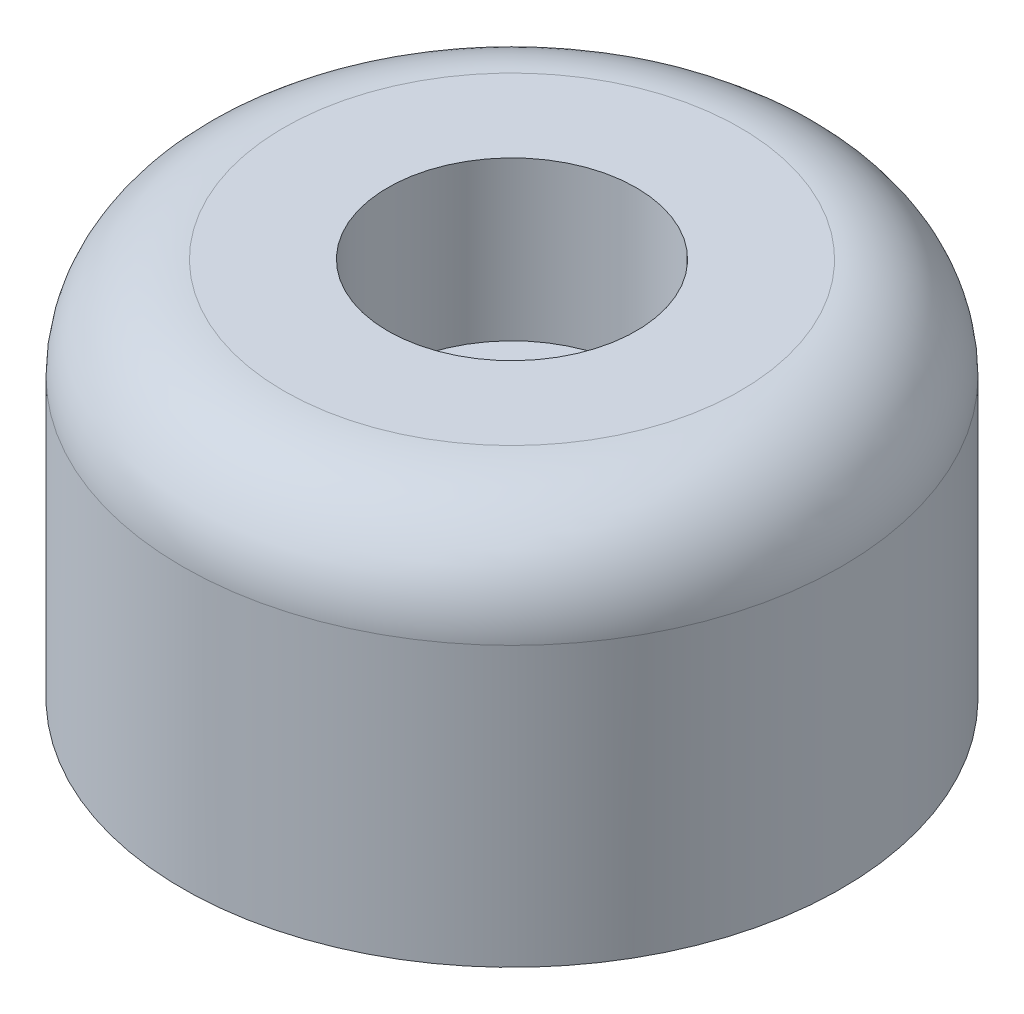
SolidWorks part; units mm, degrees
ref_plane "Front Plane" through (0, 0, 0) normal (0, 0, 1) x (1, 0, 0)
ref_plane "Top Plane" through (0, 0, 0) normal (0, 1, 0) x (1, 0, 0)
ref_plane "Right Plane" through (0, 0, 0) normal (1, 0, 0) x (0, 0, -1)
sketch "Croquis1" plane through (0, 0, 0) normal (0, 1, 0) x (1, 0, 0)
  circle A0 centre (0, 0) radius 16.51
  dimension "D1" = 33.02
extrude "Saliente-Extruir1" add sketch "Croquis1" along normal blind 19.05
hole_wizard "Refrentado para tornillo con cabeza hueca de 5/161" positions "Croquis4" profile "Croquis3" counterbore size "5/16" standard "Ansi Inch"
sketch "Croquis4" plane through (0, 19.05, 0) normal (0, 1, 0) x (1, 0, 0)
  point P0 (0, 0)
sketch "Croquis3" plane through (0, 19.05, 0) normal (1, 0, 0) x (0, 0, 1)
  line L0 (0, 0) -> (0, 22.2133)
  line L1 (0, 22.2133) -> (4.1021, 19.7485)
  line L2 (4.1021, 19.7485) -> (4.1021, 7.9375)
  line L3 (4.1021, 7.9375) -> (6.223, 7.9375)
  line L4 (6.223, 7.9375) -> (6.223, 0)
  line L5 (6.223, 0) -> (0, 0)
  line L10 (0, 22.2133) -> (-4.1021, 19.7485) construction
  line L11 (0, -6.35) -> (0, 107.95) construction
  dimension "Diámetro de taladro" = 8.2042
  dimension "Profundidad de taladro" = 19.7485
  dimension "Diámetro de refrentado" = 12.446
  dimension "Profundidad de refrentado" = 7.9375
  dimension "Ángulo de perforador" = 118
fillet "Redondeo1" radius 5.08 1 edges at (0, 19.05, 16.51)
